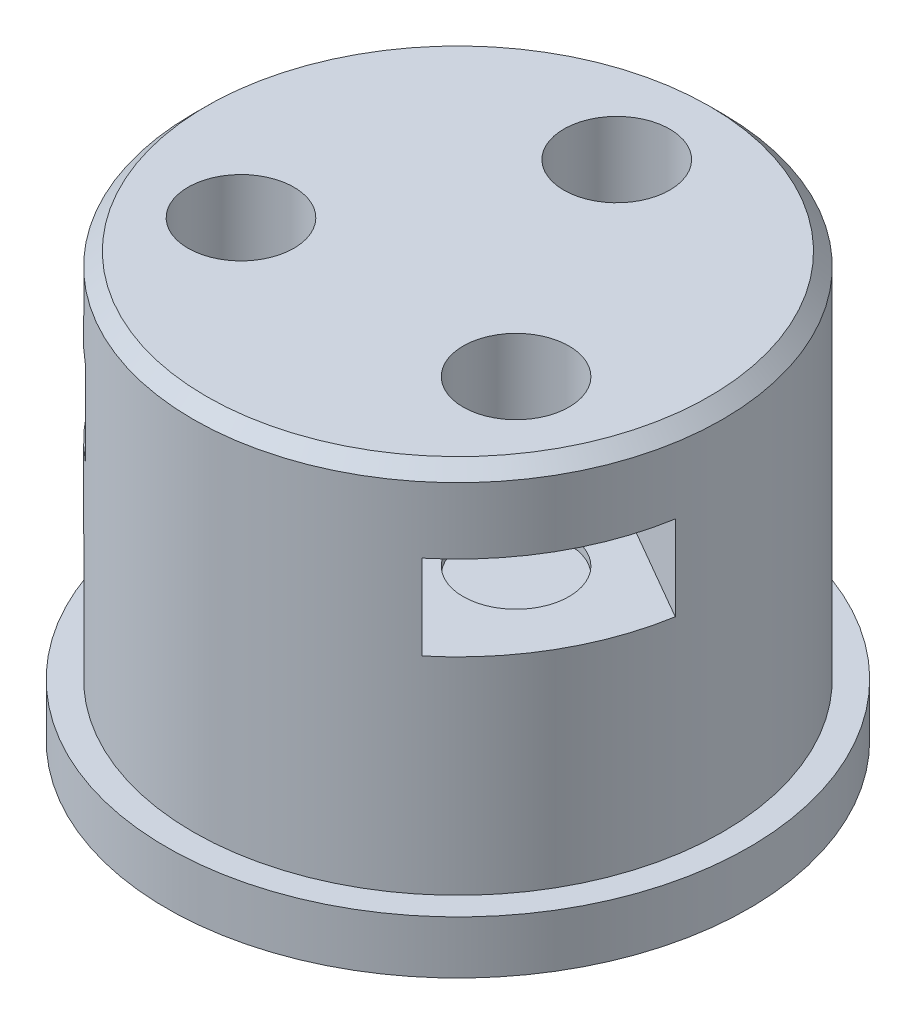
SolidWorks part; units mm, degrees
material "PLA"
ref_plane "Front Plane" through (0, 0, 0) normal (0, 0, 1) x (1, 0, 0)
ref_plane "Top Plane" through (0, 0, 0) normal (0, 1, 0) x (1, 0, 0)
ref_plane "Right Plane" through (0, 0, 0) normal (1, 0, 0) x (0, 0, -1)
sketch "Sketch1" plane through (0, 0, 0) normal (0, 1, 0) x (1, 0, 0)
  circle A0 centre (0, 0) radius 10
  circle A1 centre (0, 0) radius 8 construction
  dimension "D1" = 20
  dimension "D2" = 16
extrude "Boss-Extrude1" add sketch "Sketch1" along normal blind 16
sketch "Sketch2" plane through (0, 0, 0) normal (0, -1, 0) x (1, 0, 0)
  circle A0 centre (0, 0) radius 10 construction
  circle A1 centre (0, 0) radius 10
  circle A2 centre (0, 0) radius 11
  dimension "D1" = 1
extrude "Boss-Extrude2" add sketch "Sketch2" against normal blind 2
sketch "Sketch3" plane through (0, 0, 0) normal (0, -1, 0) x (1, 0, 0)
  circle A0 centre (0, 0) radius 8
  dimension "D1" = 16
extrude "Cut-Extrude1" cut sketch "Sketch3" against normal blind 6.5
sketch "Sketch4" plane through (0, 16, 0) normal (0, 1, 0) x (1, 0, 0)
  circle A0 centre (0, 0) radius 6 construction
  circle A1 centre (0, 6) radius 2
  circle A2 centre (5.1962, -3) radius 2
  circle A3 centre (-5.1962, -3) radius 2
  point P14 (0, 0)
  dimension "D1" = 12
  dimension "D2" = 4
  dimension "D3" = 3
extrude "Cut-Extrude2" cut sketch "Sketch4" against normal blind 6.5
sketch "Sketch5" plane through (0, 16, 0) normal (0, 1, 0) x (1, 0, 0)
  line L0 (-3.5, 8.0207) -> (-3.5, 9.3675)
  line L1 (0, 1.9585) -> (3.5, 3.9793)
  line L2 (3.5, 3.9793) -> (3.5, 8.0207)
  line L3 (3.5, 8.0207) -> (0, 10.0415)
  line L4 (0, 10.0415) -> (-3.5, 8.0207)
  line L5 (-3.5, 8.0207) -> (-3.5, 3.9793)
  line L6 (-3.5, 3.9793) -> (0, 1.9585)
  line L7 (3.5, 8.0207) -> (3.5, 9.3675)
  line L8 (8.6962, -0.9793) -> (9.8625, -1.6527)
  line L9 (8.6962, -0.9793) -> (5.1962, 1.0415)
  line L10 (8.6962, -5.0207) -> (8.6962, -0.9793)
  line L11 (5.1962, -7.0415) -> (8.6962, -5.0207)
  line L12 (5.1962, -7.0415) -> (6.3625, -7.7148)
  line L13 (1.6962, -5.0207) -> (5.1962, -7.0415)
  line L14 (1.6962, -0.9793) -> (1.6962, -5.0207)
  line L15 (5.1962, 1.0415) -> (1.6962, -0.9793)
  line L16 (-5.1962, -7.0415) -> (-6.3625, -7.7148)
  line L17 (-5.1962, -7.0415) -> (-1.6962, -5.0207)
  line L18 (-8.6962, -5.0207) -> (-5.1962, -7.0415)
  line L19 (-8.6962, -0.9793) -> (-8.6962, -5.0207)
  line L20 (-8.6962, -0.9793) -> (-9.8625, -1.6527)
  line L21 (-5.1962, 1.0415) -> (-8.6962, -0.9793)
  line L22 (-1.6962, -0.9793) -> (-5.1962, 1.0415)
  line L23 (-1.6962, -5.0207) -> (-1.6962, -0.9793)
  circle A0 centre (0, 6) radius 3.5 construction
  circle A1 centre (0, 0) radius 6 construction
  circle A3 centre (-5.1962, -3) radius 2
  circle A4 centre (-5.1962, -3) radius 2
  circle A5 centre (5.1962, -3) radius 2
  circle A6 centre (5.1962, -3) radius 2
  circle A7 centre (0, 6) radius 2
  circle A8 centre (0, 6) radius 2
  circle A9 centre (0, 0) radius 10 construction
  circle A10 centre (0, 0) radius 10
  point P50 (0, 0)
  circle M11 centre (0, 6) radius 2
  circle M12 centre (5.1962, -3) radius 2
  circle M13 centre (-5.1962, -3) radius 2
  circle M15 centre (0, 0) radius 10
  dimension "D5" = 7
  dimension "D4" = 0
  dimension "D6" = 3
extrude "Cut-Extrude3" cut sketch "Sketch5" against normal blind 3.2 from offset 3 contours L18 L16 M15 | L17 L23 L22 L21 L19 L18 M15 M13 | L19 L20 M15 | L5 L6 L1 L2 L3 L4 M15 M11 | L4 L0 M15 | L3 L7 M15 | L10 L8 M15 | L9 L15 L14 L13 L11 L10 M15 M12 | L11 L12 M15 offset against normal yes
sketch "Sketch6" plane through (0, 0, 0) normal (0, -1, 0) x (1, 0, 0)
  circle A0 centre (0, 0) radius 8
  circle A1 centre (0, 0) radius 7
  circle A2 centre (0, 0) radius 8 construction
  dimension "D1" = 1
extrude "Boss-Extrude3" add sketch "Sketch6" against normal up to surface (1.5 mm away) from offset 5 up to face at (0, 6.5, -8) offset against normal yes
chamfer "Chamfer1" distance 0.5 angle 45 1 edges at (0, 16, 10)
equation "\"Ns\" = 66"
equation "\"Np_b\" = 39"
equation "\"Np_s\" = 33"
equation "\"Nr_b\" = 144"
equation "\"module\" = 0.5"
equation "\"pressure_angle\" = 20.0"
equation "\"h_a\" = 0.5"
equation "\"h_f\" = 0.625"
equation "\"clr_tip_root\" = 0.125"
equation "\"dp_r_b\" = 72.0"
equation "\"db_r_b\" = 67.65786869658541"
equation "\"fw_r_b\" = 18.602610884769575"
equation "\"alpha_r_b\" = 0.8539582918412343"
equation "\"beta_r_b\" = 2.9579165836824686"
equation "\"bearing_ID\" = 60"
equation "\"bearing_OD\" = 78"
equation "\"bearing_height\" = 10"
equation "\"clearance_planet\" = 1.5"
equation "\"case_dist\" = 6.5"
equation "\"Motor_case_OD_max\" = 96.5"
equation "\"case_mounting_PCD\" = 89.0"
equation "\"bearing mount thickness\" = 8"
equation "\"case_mounting_hole_dia\" = 3"
equation "\"output_mounting_PCD\" = 86"
equation "\"output_mounting_hole_dia\" = 4"
equation "\"clearance_case_mount_holes_shell_thickness\" = 1"
equation "\"motor_case_OD_base\" = 87.0"
equation "\"sec_carrier_thickness\" = 5"
equation "\"sun_coupler_hub_thickness\" = 4"
equation "\"clearance_sun_coupler_sec_carrier\" = 1.5"
equation "\"clearance_motor_and_case\" = 5.0"
equation "\"motor_OD\" = 72"
equation "\"Motor_case_thickness\" = 2.5"
equation "\"Motor_case_ID\" = 82.0"
equation "\"case_mounting_hole_shift\" = 1.0"
equation "\"output_mounting_nut_wrench_size\" = 7"
equation "\"output_mounting_nut_thickness\" = 3.2"
equation "\"case_mounting_hole_allen_socket_dia\" = 5.5"
equation "\"output_mounting_nut_depth\" = 3"
equation "\"case_mounting_bolt_depth\" = 4.5"
equation "\"ring_radial_thickness\" = 5"
equation "\"ring_OD_b\" = 82.0"
equation "\"ring_to_chamfer_clearance\" = 1.5"
equation "\"Motor_case_OD_base_to_chamfer\" = 5"
equation "\"pattern_offset_from_motor_case_OD_base\" = 3"
equation "\"pattern_bulge_dia\" = 3"
equation "\"pattern_num_bulge\" = 18"
equation "\"pattern_depth\" = 2"
equation "\"motor_height\" = 27"
equation "\"case_mounting_wrench_size\" = 5.5"
equation "\"case_mounting_nut_clearance\" = 2"
equation "\"base_plate_thickness\" = 4"
equation "\"case_mounting_nut_thickness\" = 2.4"
equation "\"case_mounting_surface_height\" = 4"
equation "\"motor_mount_hole_PCD\" = 32"
equation "\"motor_mount_hole_dia\" = 4"
equation "\"motor_mount_hole_num\" = 4"
equation "\"central_hole_offset_from_motor_mount_PCD\" = 5"
equation "\"wire_slot_dist_from_center\" = 26"
equation "\"wire_slot_length\" = 10"
equation "\"wire_slot_radius\" = 2.5"
equation "\"driver_upper_holes_dist_from_center\" = 29"
equation "\"driver_lower_holes_dist_from_center\" = 13"
equation "\"driver_side_holes_dist_from_center\" = 22.5"
equation "\"driver_mount_holes_dia\" = 3"
equation "\"driver_mount_inserts_OD\" = 4.8"
equation "\"driver_mount_thickness\" = 1.5"
equation "\"driver_mount_height\" = 6"
equation "\"air_flow_hole_offset\" = 3"
equation "\"pressure angle\" = 20.0"
equation "\"h_b\" = 0.625"
equation "\"fw_p_s\" = 22.55792585723615"
equation "\"num_planet\" = 6"
equation "\"planet_pin_bolt_dia\" = 5"
equation "\"planet_pin_socket_head_dia\" = 8.5"
equation "\"carrier_PCD\" = 52.5"
equation "\"planet_shaft_dia\" = 8"
equation "\"planet_shaft_step_offset\" = 1"
equation "\"carrier_trapezoidal_support_sun_offset\" = 5"
equation "\"carrier_trapezoidal_support_hole_PCD_offset_bearing_ID\" = 4"
equation "\"carrier_trapezoidal_support_hole_dia\" = 3"
equation "\"carrier_trapezoidal_support_hole_socket_head_dia\" = 5.5"
equation "\"carrier_bearing_step_width\" = 1.5"
equation "\"standard_clearance_1_5mm\" = 1.5"
equation "\"standard_fillet_1_5mm\" = 1.5"
equation "\"sun_shaft_bearing_OD\" = 16"
equation "\"sun_shaft_bearing_width\" = 5"
equation "\"standard_bearing_insertion_chamfer\" = 0.5"
equation "\"carrier_trapezoidal_support_hole_wrench_size\" = 5.5"
equation "\"planet_pin_bolt_wrench_size\" = 8"
equation "\"planet_bearing_OD\" = 12"
equation "\"planet_bearing_width\" = 3.5"
equation "\"planet_bore\" = 10"
equation "\"motor_output_hole_PCD\" = 22"
equation "\"motor_output_hole_dia\" = 3"
equation "\"motor_output_hole_num\" = 4"
equation "\"dp_s\" = 33.0"
equation "\"db_s\" = 31.00985648593498"
equation "\"fw_s_calc\" = 1.5726146484026726"
equation "\"alpha_s\" = 0.8539582918412449"
equation "\"beta_s\" = 1.0193561435902372"
equation "\"dp_p_b\" = 19.5"
equation "\"db_p_b\" = 18.324006105325214"
equation "\"alpha_p_b\" = 0.8539582918412414"
equation "\"beta_p_b\" = 2.907468031702132"
equation "\"sun_shaft_bearing_ID\" = 8"
equation "\"sun_hub_dia\" = 28.0"
equation "\"sun_central_bolt_dia\" = 5"
equation "\"sun_central_bolt_socket_head_dia\" = 8.5"
equation "\"fw_s_used\" = 48.660536742005725"
equation "\"motor_output_hole_CSK_OD\" = 6"
equation "\"motor_output_hole_CSK_head_height\" = 1.5"
equation "\"bearing_retainer_thickness\" = 2"
equation "\"fw_p_b\" = 18.602610884769575"
equation "\"dp_p_s\" = 16.5"
equation "\"db_p_s\" = 15.50492824296749"
equation "\"alpha_p_s\" = 0.8539582918412449"
equation "\"beta_p_s\" = 3.7466288708629643"
equation "\"Nr_s\" = 138"
equation "\"clr_tip_root_s\" = 0.125"
equation "\"dp_r_s\" = 69.0"
equation "\"db_r_s\" = 64.83879083422768"
equation "\"fw_r_s\" = 21.05792585723615"
equation "\"alpha_r_s\" = 0.8539582918412485"
equation "\"beta_r_s\" = 3.0122644097694535"
equation "\"D1@Boss-Extrude1\"=\"bearing_height\" + \"carrier_thickness\" + \"carrier_small_ring_inner_bearing_flap\""
equation "\"D1@Cut-Extrude1\"=\"sun_shaft_bearing_width\" + \"standard_clearance_1_5mm\""
equation "\"D5@Sketch5\"=\"small_ring_output_wall_to_bearing_shaft_attachement_nut_wrench\""
equation "\"small_ring_case_thickness\" = 4"
equation "\"carrier_thickness\" = 4"
equation "\"small_ring_output_wall_thickness\" = 5"
equation "\"small_ring_output_wall_to_bearing_shaft_attachement_hole_dia\" = 4"
equation "\"small_ring_output_wall_to_bearing_shaft_attachement_hole_pcd\" = 12"
equation "\"small_ring_output_wall_to_bearing_shaft_attachement_hole_num\" = 3"
equation "\"small_ring_output_wall_to_bearing_shaft_attachement_hole_CSK_OD\" = 8"
equation "\"small_ring_output_wall_to_bearing_shaft_attachement_hole_CSK_head_height\" = 2.0"
equation "\"carrier_small_ring_inner_bearing_ID\" = 20"
equation "\"carrier_small_ring_inner_bearing_OD\" = 32"
equation "\"carrier_small_ring_inner_bearing_height\" = 7"
equation "\"D1@Sketch1\"=\"carrier_small_ring_inner_bearing_ID\""
equation "\"D2@Sketch1\"=\"sun_shaft_bearing_OD\""
equation "\"D1@Sketch2\"=\"standard_clearance_1_5mm\"*2/3"
equation "\"D1@Sketch3\"=\"sun_shaft_bearing_OD\""
equation "\"D1@Sketch4\"=\"small_ring_output_wall_to_bearing_shaft_attachement_hole_pcd\""
equation "\"D2@Sketch4\"=\"small_ring_output_wall_to_bearing_shaft_attachement_hole_dia\""
equation "\"D3@Sketch4\"=\"small_ring_output_wall_to_bearing_shaft_attachement_hole_num\""
equation "\"D6@Sketch5\"=\"small_ring_output_wall_to_bearing_shaft_attachement_hole_num\""
equation "\"D19@Cut-Extrude3\"=\"standard_clearance_1_5mm\"*2"
equation "\"D1@Sketch6\"=\"standard_clearance_1_5mm\"*2/3"
equation "\"D19@Boss-Extrude3\"=\"sun_shaft_bearing_width\""
equation "\"small_ring_output_wall_to_bearing_shaft_attachement_hole_depth\" = 6.5"
equation "\"small_ring_output_wall_to_bearing_shaft_attachement_nut_wrench\" = 7"
equation "\"small_ring_output_wall_to_bearing_shaft_attachement_nut_thickness\" = 3.2"
equation "\"carrier_small_ring_inner_bearing_flap\" = 2"
equation "\"D1@Boss-Extrude2\"=\"carrier_small_ring_inner_bearing_flap\""
equation "\"D1@Cut-Extrude2\"=\"small_ring_output_wall_to_bearing_shaft_attachement_hole_depth\""
equation "\"D1@Cut-Extrude3\"=\"small_ring_output_wall_to_bearing_shaft_attachement_nut_thickness\""
equation "\"D1@Chamfer1\"=\"standard_bearing_insertion_chamfer\""
